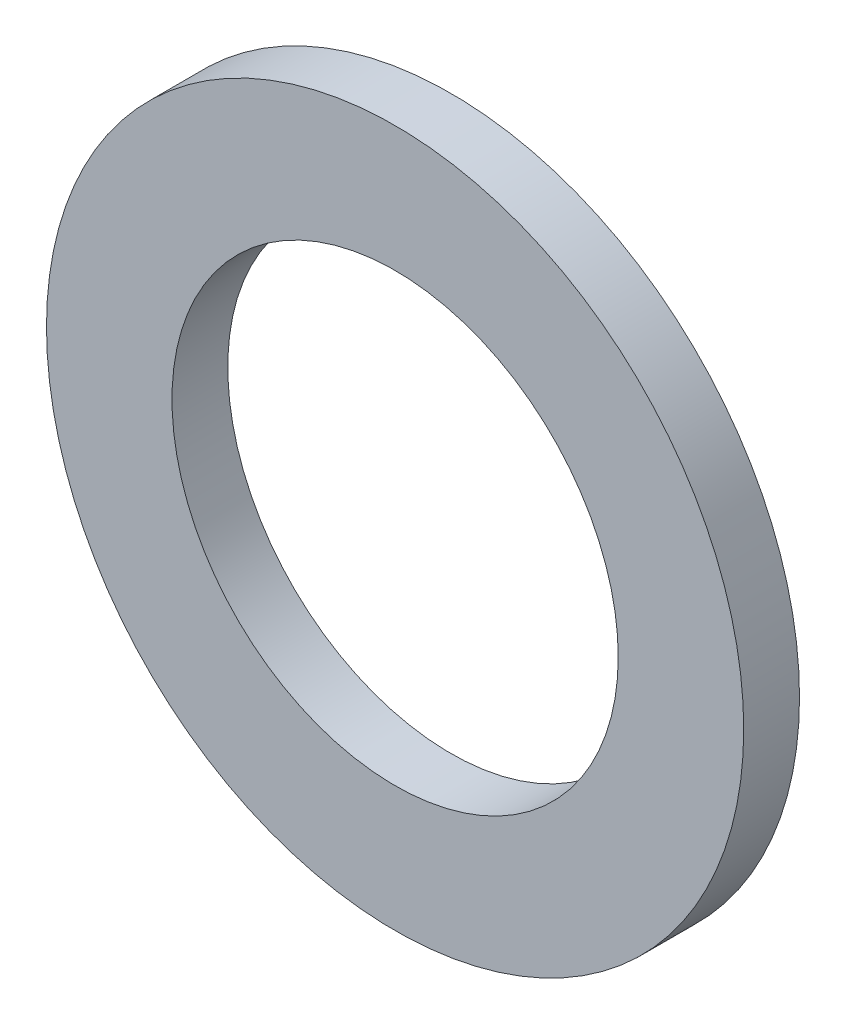
SolidWorks part; units mm, degrees
material "AISI 1035 Steel (SS)"
ref_plane "Front Plane" through (0, 0, 0) normal (0, 0, 1) x (1, 0, 0)
ref_plane "Top Plane" through (0, 0, 0) normal (0, 1, 0) x (1, 0, 0)
ref_plane "Right Plane" through (0, 0, 0) normal (1, 0, 0) x (0, 0, -1)
sketch "Sketch1" plane through (0, 0, 0) normal (0, 0, 1) x (1, 0, 0)
  circle A0 centre (0, 0) radius 19.8438
  circle A1 centre (0, 0) radius 12.7
  dimension "D1" = 25.4
  dimension "D2" = 39.6875
extrude "Boss-Extrude1" add sketch "Sketch1" along normal blind 3.175
